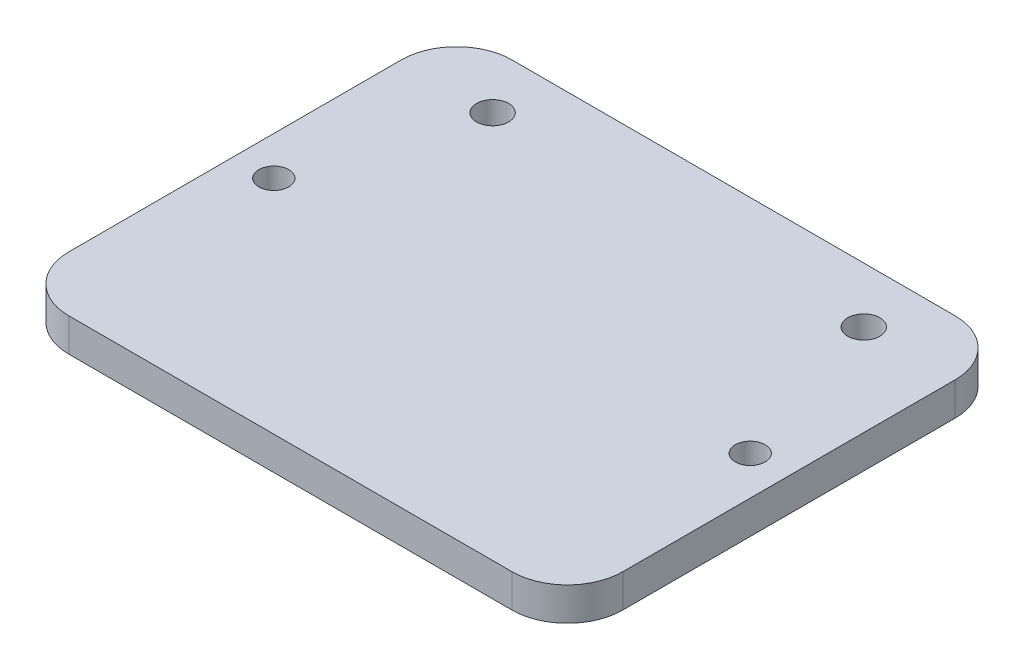
SolidWorks part; units mm, degrees
ref_plane "Front Plane" through (0, 0, 0) normal (0, 0, 1) x (1, 0, 0)
ref_plane "Top Plane" through (0, 0, 0) normal (0, 1, 0) x (1, 0, 0)
ref_plane "Right Plane" through (0, 0, 0) normal (1, 0, 0) x (0, 0, -1)
sketch "Sketch1" plane through (0, 0, 0) normal (0, 1, 0) x (1, 0, 0)
  line L0 (8.25, 35) -> (41.75, 35) construction
  line L1 (0, 40) -> (50, 40)
  line L2 (0, 40) -> (0, 0)
  line L3 (0, 0) -> (50, 0)
  line L4 (50, 40) -> (50, 0)
  line L5 (3.5, 20) -> (46.5, 20) construction
  point P4 (25, 35)
  point P6 (8.25, 35)
  point P7 (41.75, 35)
  point P8 (25, 40)
  point P10 (3.5, 20)
  point P11 (46.5, 20)
  point P14 (25, 20)
  dimension "D1" = 33.5
  dimension "D2" = 50
  dimension "D3" = 40
  dimension "D4" = 5
  dimension "D5" = 43
  dimension "D6" = 15
extrude "Boss-Extrude1" add sketch "Sketch1" along normal blind 3
hole_wizard "M2.5 Clearance Hole1" positions "Sketch2" profile "Sketch3" hole size "M2.5" standard "ANSI Metric"
sketch "Sketch2" plane through (0, 3, 0) normal (0, 1, 0) x (1, 0, 0)
  point P0 (8.25, 35)
  point P3 (41.75, 35)
sketch "Sketch3" plane through (8.25, 3, -35) normal (1, 0, 0) x (0, 0, 1)
  line L0 (0, 0) -> (0, 16.1112)
  line L1 (0, 16.1112) -> (1.45, 15.24)
  line L2 (1.45, 15.24) -> (1.45, 0)
  line L5 (1.45, 0) -> (0, 0)
  line L10 (0, 16.1112) -> (-1.45, 15.24) construction
  line L11 (0, -6.35) -> (0, 107.95) construction
  dimension "Hole Dia." = 2.9
  dimension "Hole Depth" = 15.24
  dimension "Drill Angle" = 118
hole_wizard "M2.5 Clearance Hole2" positions "Sketch4" profile "Sketch5" hole size "M2.5" standard "ANSI Metric"
sketch "Sketch4" plane through (0, 3, 0) normal (0, 1, 0) x (1, 0, 0)
  point P0 (3.5, 20)
  point P3 (46.5, 20)
sketch "Sketch5" plane through (3.5, 3, -20) normal (1, 0, 0) x (0, 0, 1)
  line L0 (0, 0) -> (0, 16.0512)
  line L1 (0, 16.0512) -> (1.35, 15.24)
  line L2 (1.35, 15.24) -> (1.35, 0)
  line L5 (1.35, 0) -> (0, 0)
  line L10 (0, 16.0512) -> (-1.35, 15.24) construction
  line L11 (0, -6.35) -> (0, 107.95) construction
  dimension "Hole Dia." = 2.7
  dimension "Hole Depth" = 15.24
  dimension "Drill Angle" = 118
fillet "Fillet1" radius 5 4 edges at (0, 1.5, 0) (50, 1.5, -40) (50, 1.5, 0) (0, 1.5, -40)
